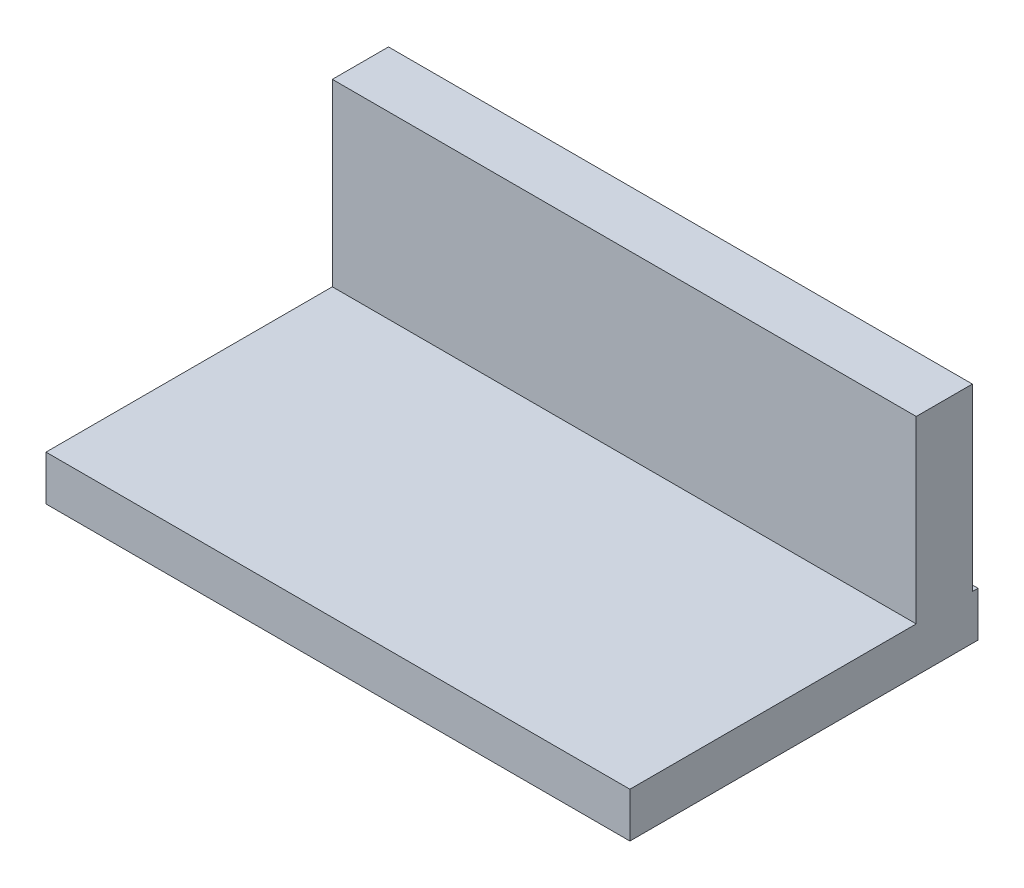
SolidWorks part; units mm, degrees
ref_plane "Front Plane" through (0, 0, 0) normal (0, 0, 1) x (1, 0, 0)
ref_plane "Top Plane" through (0, 0, 0) normal (0, 1, 0) x (1, 0, 0)
ref_plane "Right Plane" through (0, 0, 0) normal (1, 0, 0) x (0, 0, -1)
sketch "Sketch1" plane through (0, 0, 0) normal (0, 1, 0) x (1, 0, 0)
  line L1 (-13, 7.75) -> (13, 7.75)
  line L2 (-13, 7.75) -> (-13, -7.75)
  line L3 (-13, -7.75) -> (13, -7.75)
  line L4 (13, 7.75) -> (13, -7.75)
  line L5 (-13, 7.75) -> (13, -7.75) construction
  line L6 (-13, -7.75) -> (13, 7.75) construction
  point P0 (0, 0)
  dimension "D1" = 26
  dimension "D2" = 15.5
extrude "Boss-Extrude1" add sketch "Sketch1" along normal blind 2
sketch "Sketch3" plane through (0, 2, 0) normal (0, 1, 0) x (1, 0, 0)
  line L0 (-13, 7.75) -> (-13, -7.75) construction
  line L1 (-13, 7.5) -> (13, 7.5)
  line L2 (-13, 7.5) -> (-13, 5)
  line L3 (-13, 5) -> (13, 5)
  line L4 (13, 7.5) -> (13, 5)
  line L5 (13, 7.75) -> (-13, 7.75) construction
  point P4 (-13, 4.87)
  dimension "D1" = 2.5
  dimension "D2" = 26
  dimension "D3" = 0.25
extrude "Boss-Extrude2" add sketch "Sketch3" along normal blind 8
